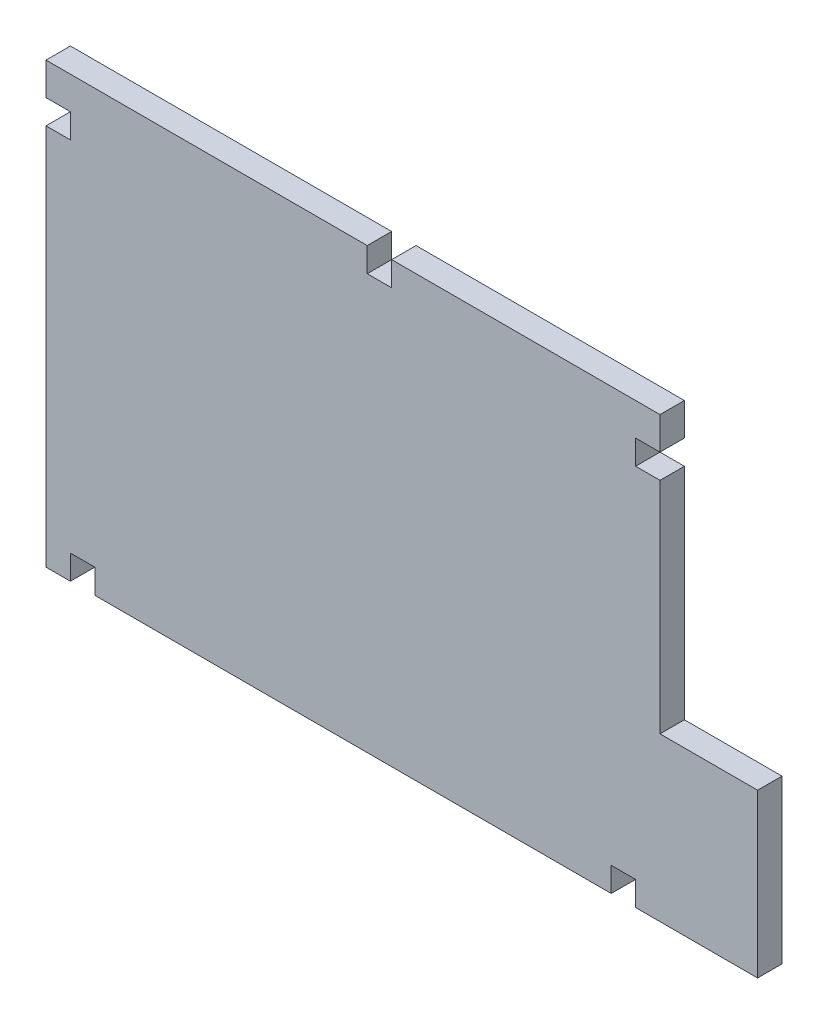
SolidWorks part; units mm, degrees
ref_plane "前视基准面" through (0, 0, 0) normal (0, 0, 1) x (1, 0, 0)
ref_plane "上视基准面" through (0, 0, 0) normal (0, 1, 0) x (1, 0, 0)
ref_plane "右视基准面" through (0, 0, 0) normal (1, 0, 0) x (0, 0, -1)
other "Configuration Table"
sketch "草图1" plane through (0, 0, 0) normal (0, 0, 1) x (1, 0, 0)
  line L0 (0, 0) -> (0, -4)
  line L1 (0, -4) -> (3, -4)
  line L2 (3, -4) -> (3, -7)
  line L3 (3, -7) -> (0, -7)
  line L4 (0, -7) -> (0, -54)
  line L5 (0, -54) -> (3, -54)
  line L6 (3, -54) -> (3, -51)
  line L7 (3, -51) -> (6, -51)
  line L8 (6, -51) -> (6, -54)
  line L9 (6, -54) -> (69.5, -54)
  line L10 (69.5, -54) -> (69.5, -51)
  line L11 (69.5, -51) -> (72.5, -51)
  line L12 (72.5, -51) -> (72.5, -54)
  line L13 (72.5, -54) -> (87.5, -54)
  line L14 (87.5, -54) -> (87.5, -34)
  line L15 (87.5, -34) -> (75.5, -34)
  line L16 (0, 0) -> (39.5, 0)
  line L17 (39.5, 0) -> (39.5, -3)
  line L18 (39.5, -3) -> (42.5, -3)
  line L19 (42.5, -3) -> (42.5, 0)
  line L20 (42.5, 0) -> (75.5, 0)
  line L21 (75.5, 0) -> (75.5, -4)
  line L22 (75.5, -4) -> (72.5, -4)
  line L23 (72.5, -4) -> (72.5, -7)
  line L24 (72.5, -7) -> (75.5, -7)
  line L25 (75.5, -7) -> (75.5, -34)
  dimension "D8" = 3
  dimension "D11" = 3
  dimension "D14" = 12
  dimension "D1" = 4
  dimension "D2" = 3
  dimension "D3" = 3
  dimension "D4" = 3
  dimension "D5" = 47
  dimension "D6" = 3
  dimension "D7" = 3
  dimension "D9" = 63.5
  dimension "D10" = 3
  dimension "D12" = 15
  dimension "D13" = 20
  dimension "D15" = 39.5
  dimension "D16" = 3
  dimension "D17" = 3
  dimension "D18" = 4
extrude "凸台-拉伸1" add sketch "草图1" along normal blind 3
